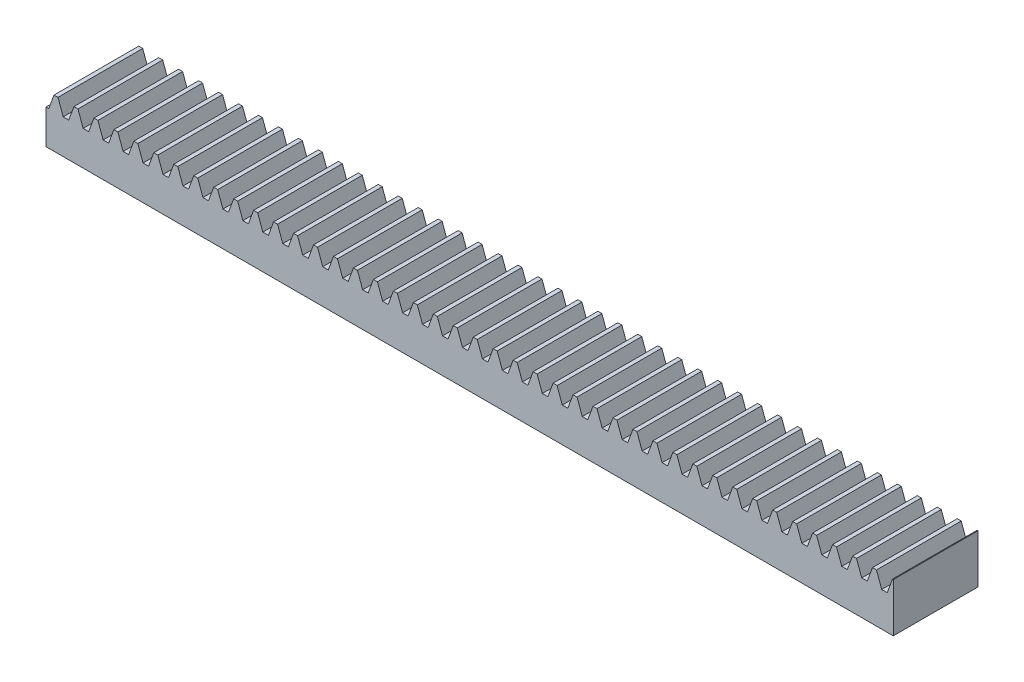
SolidWorks part; units mm, degrees
extrude "Blank" add sketch "BlankSke" against normal blind 20
sketch "BlankSke" plane through (0, 0, 0) normal (0, 0, 1) x (1, 0, 0)
  line L1 (0, 0) -> (200, 0)
  line L2 (0, 0) -> (0, 11.5)
  line L3 (0, 11.5) -> (200, 11.5)
  line L4 (200, 0) -> (200, 11.5)
  dimension "Length" = 200
  dimension "Blank_height" = 11.5
ref_plane "Plane1" through (0, 0, 0) normal (0, 0, 1) x (1, 0, 0)
ref_plane "Plane2" through (0, 0, 0) normal (0, 1, 0) x (1, 0, 0)
ref_plane "Plane3" through (0, 0, 0) normal (1, 0, 0) x (0, 0, -1)
sketch "HoldingSke" plane through (0, 0, 0) normal (0, 1, 0) x (1, 0, 0)
  line L0 (0, 0) -> (0.0928, 0.6602)
  line L1 (-15, 0) -> (100, 0) construction
  line L2 (0, 0) -> (-2.1039, 2.3779)
  line L3 (0, 0) -> (-11.863, 4.5341)
  line L4 (0, 0) -> (6.2122, 5.9991)
  line L5 (0, 0) -> (-23.7986, -8.8762)
  line L6 (0, 0) -> (-10.5278, -7.1032)
  line L9 (-71.009, 38.7566) -> (116.9296, 107.1606)
  line L10 (-76.2, 3.8779) -> (-66.2, 3.8779)
  line L11 (0, 0) -> (-20, 0)
  line L12 (-76.2, 101.6) -> (-76.147, 101.6)
  line L13 (24.9733, 27.94) -> (52.9518, 28.4284)
  line L14 (24.9733, 27.94) -> (24.9743, 27.94)
  line L15 (24.9733, 27.94) -> (100.4006, 29.5858)
  circle A0 centre (0, 0) radius 19.05
  circle A1 centre (0, 0) radius 5
  circle A2 centre (0, 0) radius 12.7
  dimension "MPH" = 10
  dimension "Diameter" = 38.1
  dimension "Num_teeth" = 44
  dimension "Pitch" = 0.6667
  dimension "Show_teeth" = 998
  dimension "Thickness" = 12.7
  dimension "Ap" = 20
  dimension "Pitch_height" = 10
  dimension "Width" = 20
  dimension "Backlash" = 0.053
  dimension "Addendum_fac" = 1
  dimension "Dedendum_fac" = 1.25
  dimension "Clearance_fac" = 0.25
  dimension "Dedendum_add" = 0.001
  dimension "Length" = 200
  dimension "Module" = 1.5
sketch "TooCutSkeIll" plane through (0, 0, 0) normal (0, 0, 1) x (1, 0, 0)
  line L0 (-1.8687, 11.4605) -> (-0.7447, 8.3724)
  line L1 (-0.3914, 8.125) -> (0.3914, 8.125)
  line L2 (0.7447, 8.3724) -> (1.8687, 11.4605)
  line L3 (200, 11.5) -> (0, 11.5) construction
  line L4 (0, 0) -> (0, 64.897) construction
  line L5 (-13.208, 10) -> (12.954, 10) construction
  line L6 (0, 0) -> (200, 0) construction
  line L7 (1.3371, 10) -> (1.3371, 48.7463) construction
  line L8 (-1.3371, 10) -> (-1.3371, 48.7463) construction
  line L9 (1.9251, 11.5) -> (1.9251, 11.5254)
  line L10 (-1.9251, 11.5) -> (-1.9251, 11.5254)
  line L11 (-1.9251, 11.5254) -> (1.9251, 11.5254)
  arc A0 (0.3914, 8.125) -> (0.7447, 8.3724) centre (0.3914, 8.501) ccw
  arc A1 (-0.7447, 8.3724) -> (-0.3914, 8.125) centre (-0.3914, 8.501) ccw
  arc A2 (1.9251, 11.5) -> (1.8687, 11.4605) centre (1.9251, 11.44) ccw
  arc A3 (-1.8687, 11.4605) -> (-1.9251, 11.5) centre (-1.9251, 11.44) ccw
  dimension "Pitch_height" = 10
  dimension "Addendum_plus" = 1.5254
  dimension "Pressure_angle" = 20
  dimension "Gap_width" = 2.6742
  dimension "Dedendum" = 1.875
extrude "ToothCutIll" [suppressed] cut sketch "TooCutSkeIll" against normal through all
sketch "TooCutSkeSim" plane through (0, 0, 0) normal (0, 0, 1) x (1, 0, 0)
  line L0 (0.6547, 8.125) -> (-0.6547, 8.125)
  line L1 (1.8923, 11.5254) -> (0.6547, 8.125)
  line L2 (0, 17.4625) -> (0, 53.467) construction
  line L3 (1.8923, 11.5254) -> (-1.8923, 11.5254)
  line L6 (-1.8923, 11.5254) -> (-0.6547, 8.125)
  line L9 (-1.3371, 10) -> (1.3371, 10) construction
  line L10 (0, 0) -> (200, 0) construction
  line L11 (1.3371, 10) -> (1.3371, 53.467) construction
  line L12 (-1.3371, 10) -> (-1.3371, 53.467) construction
  dimension "Pitch_height" = 10
  dimension "Addendum_plus" = 1.5254
  dimension "Pressure_angle" = 20
  dimension "Gap_width" = 2.6742
  dimension "Dedendum" = 1.875
extrude "ToothCutSim" cut sketch "TooCutSkeSim" against normal through all
pattern_linear "TeethCuts" count 43 spacing 4.7124 along (1, 0, 0) of "ToothCutIll", "ToothCutSim"
equation "' \"Module@HoldingSke\" = 6.35"
equation "' \"Num_teeth@HoldingSke\" = 12"
equation "' \"Ap@HoldingSke\" =  20"
equation "' \"Ap@HoldingSke\" = 20"
equation "' \"Width@HoldingSke\" = 0.25 * 25.4"
equation "' \"Show_teeth@HoldingSke\" = 500"
equation "' \"Backlash@HoldingSke\" = 0.009 * 25.4"
equation "' \"Addendum_fac@HoldingSke\" = 1.0"
equation "' \"Dedendum_fac@HoldingSke\" = 1.25"
equation "' \"Dedendum_add@HoldingSke\" = 0.00005 * 25.4"
equation "' \"Clearance_fac@HoldingSke\" = 0.25"
equation "' \"Pitch_height@HoldingSke\" = 1 * 25.4"
equation "' \"Length@HoldingSke\" = 4.71 * 25.4"
equation "\"Pitch@HoldingSke\" = 1 / \"Module@HoldingSke\""
equation "\"MPH@HoldingSke\" = \"Dedendum_fac@HoldingSke\" / \"Pitch@HoldingSke\" + 2 * \"Dedendum_add@HoldingSke\" + 0.002 * 25.4"
equation "\"MPH@HoldingSke\" = ((sgn( \"MPH@HoldingSke\" - \"Pitch_height@HoldingSke\")+1)*( \"MPH@HoldingSke\" - \"Pitch_height@HoldingSke\"))/2 + \"Pitch_height@HoldingSke\""
equation "\"Blank_height@BlankSke\" = \"Pitch_height@HoldingSke\" + \"Addendum_fac@HoldingSke\"  / \"Pitch@HoldingSke\" "
equation "\"Length@BlankSke\" =  \"Length@HoldingSke\""
equation "\"Face_width@Blank\" = \"Width@HoldingSke\""
equation "\"Pressure_angle@TooCutSkeIll\" = \"Ap@HoldingSke\""
equation "\"Addendum_plus@TooCutSkeIll\" =  \"Addendum_fac@HoldingSke\"  / \"Pitch@HoldingSke\" + 0.001 *25.4"
equation "\"Dedendum@TooCutSkeIll\" = \"Dedendum_fac@HoldingSke\"  / \"Pitch@HoldingSke\""
equation "\"Pitch_height@TooCutSkeIll\" =  \"MPH@HoldingSke\""
equation "\"Gap_width@TooCutSkeIll\" = 3.14159265 / 2 / \"Pitch@HoldingSke\" + 6 * \"Backlash@HoldingSke\""
equation "\"Pressure_angle@TooCutSkeSim\" = \"Ap@HoldingSke\""
equation "\"Addendum_plus@TooCutSkeSim\" =  \"Addendum_fac@HoldingSke\"  / \"Pitch@HoldingSke\" + 0.001 * 25.4"
equation "\"Dedendum@TooCutSkeSim\" = \"Dedendum_fac@HoldingSke\"  / \"Pitch@HoldingSke\""
equation "\"Pitch_height@TooCutSkeSim\" =  \"MPH@HoldingSke\""
equation "\"Gap_width@TooCutSkeSim\" = 3.14159265 / 2 / \"Pitch@HoldingSke\" + 6 * \"Backlash@HoldingSke\""
equation "\"Root_fillet@TooCutSkeIll\" = \"Clearance_fac@HoldingSke\" / \"Pitch@HoldingSke\" + \"Dedendum_add@HoldingSke\""
equation "\"Break_rad@TooCutSkeIll\" = 0.02 / \"Pitch@HoldingSke\" * 2"
equation "\"Linear_pitch@TeethCuts\" = 3.14159265 / \"Pitch@HoldingSke\""
equation "\"Num_teeth@HoldingSke\" = int( ( \"Length@HoldingSke\" + 0 ) / (3.14159265 / \"Pitch@HoldingSke\")) + 0.9999  + 1"
equation " \"Num_teeth@TeethCuts\" = int( \"Show_teeth@HoldingSke\" ) + 1"
equation " \"Num_teeth@TeethCuts\" = ((sgn( \"Num_teeth@TeethCuts\" - \"Num_teeth@HoldingSke\" )-1)*( \"Num_teeth@TeethCuts\" - \"Num_teeth@HoldingSke\" ))/-2+ \"Num_teeth@HoldingSke\""
equation " \"Num_teeth@TeethCuts\" = ((sgn( \"Num_teeth@TeethCuts\" - 2.0)+1)*( \"Num_teeth@TeethCuts\" - 2.0))/2 +2.0"
